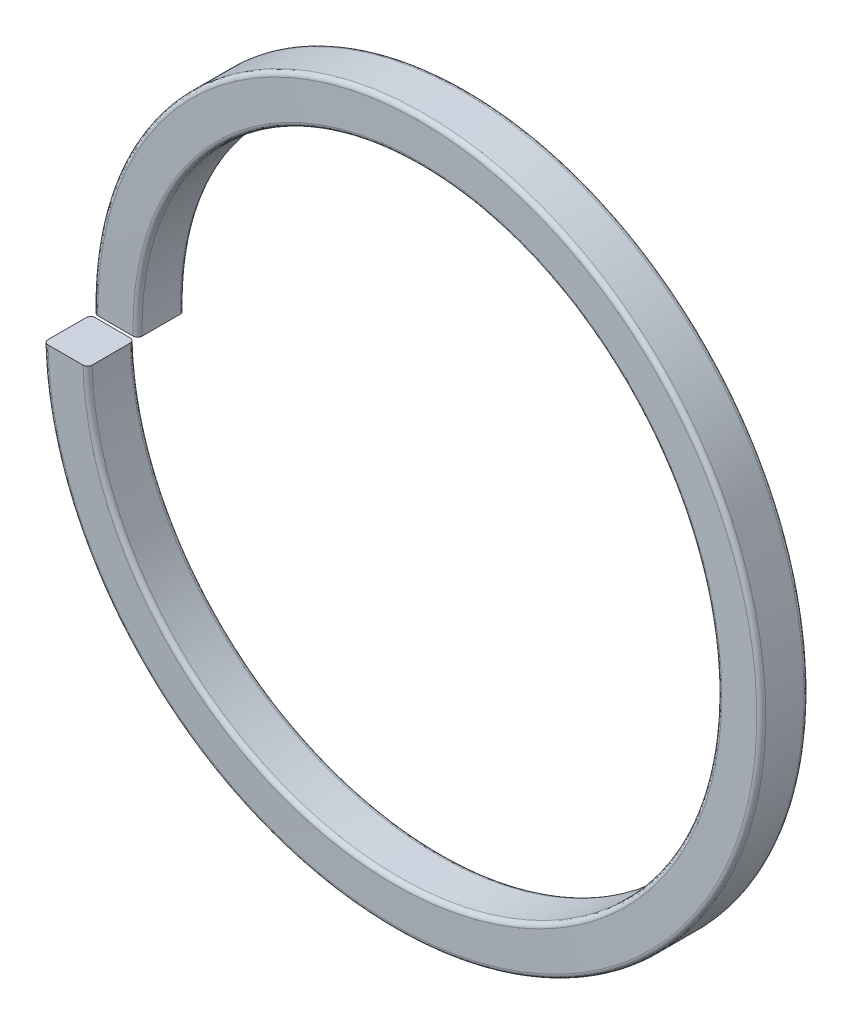
SolidWorks part; units mm, degrees
ref_plane "Front Plane" through (0, 0, 0) normal (0, 0, 1) x (1, 0, 0)
ref_plane "Top Plane" through (0, 0, 0) normal (0, 1, 0) x (1, 0, 0)
ref_plane "Right Plane" through (0, 0, 0) normal (1, 0, 0) x (0, 0, -1)
sketch "Sketch1" plane through (0, 0, 0) normal (0, 0, 1) x (1, 0, 0)
  circle A0 centre (0, 0) radius 6.5
  dimension "D1" = 13
curve "Helix/Spiral1" pitch 1 height 1 turns 1
sketch "Sketch3" plane through (0, 0, 0) normal (0, 1, 0) x (1, 0, 0)
  line L0 (-6.8263, -0.5104) -> (-6.1256, -0.5104)
  line L5 (-6.9163, -0.6004) -> (-6.9163, -1.3629)
  line L6 (-6.0356, -0.6004) -> (-6.0356, -1.3629)
  line L7 (-6.1256, -1.4529) -> (-6.8263, -1.4529)
  arc A0 (-6.8263, -0.5104) -> (-6.9163, -0.6004) centre (-6.8263, -0.6004) ccw
  arc A1 (-6.1256, -0.5104) -> (-6.0356, -0.6004) centre (-6.1256, -0.6004) cw
  arc A2 (-6.9163, -1.3629) -> (-6.8263, -1.4529) centre (-6.8263, -1.3629) ccw
  arc A3 (-6.0356, -1.3629) -> (-6.1256, -1.4529) centre (-6.1256, -1.3629) cw
  dimension "D1" = 0.09
  dimension "D2" = 0.09
  dimension "D3" = 0.09
  dimension "D4" = 0.09
sweep "Sweep4" add profiles "Sketch3" path "Helix/Spiral1"
